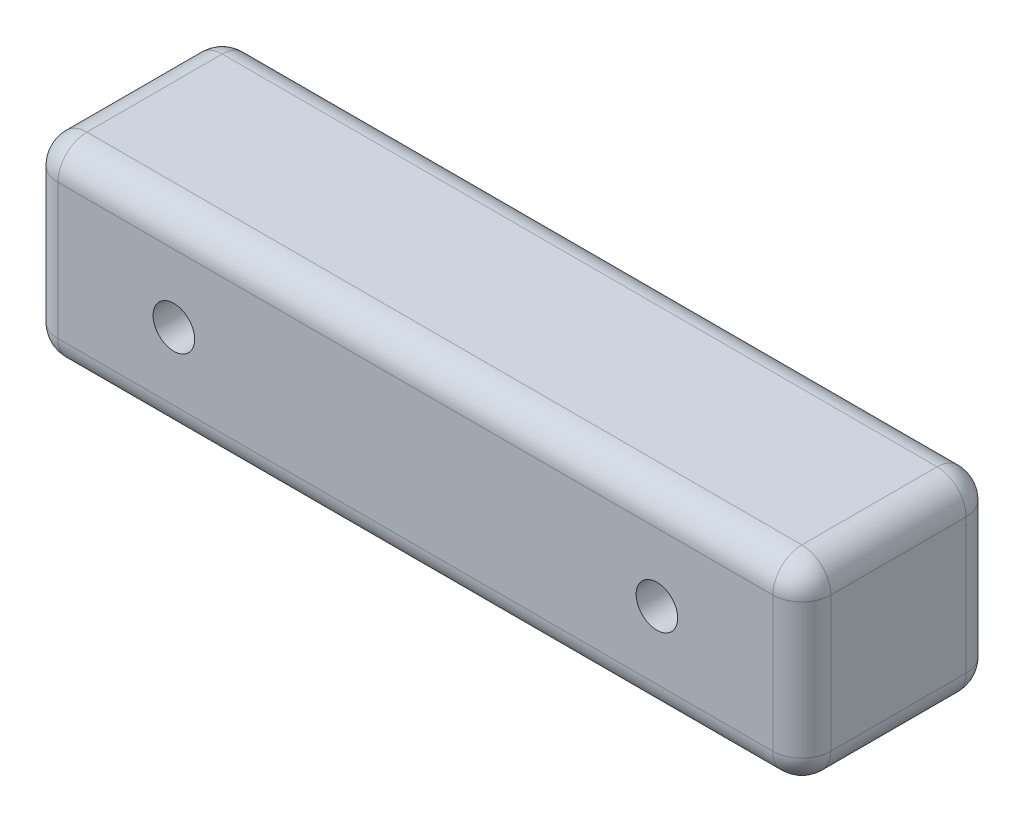
SolidWorks part; units mm, degrees
ref_plane "Alzado" through (0, 0, 0) normal (0, 0, 1) x (1, 0, 0)
ref_plane "Planta" through (0, 0, 0) normal (0, 1, 0) x (1, 0, 0)
ref_plane "Vista lateral" through (0, 0, 0) normal (1, 0, 0) x (0, 0, -1)
sketch "Croquis1" plane through (0, 0, 0) normal (0, 0, 1) x (1, 0, 0)
  line L0 (40, 0) -> (-40, 0) construction
  line L1 (-40, 10) -> (40, 10)
  line L2 (40, 10) -> (40, -10)
  line L3 (40, -10) -> (-40, -10)
  line L4 (-40, -10) -> (-40, 10)
  line L5 (0, 0) -> (0, -3.7626) construction
  circle A0 centre (25, 0) radius 2.15
  circle A1 centre (-25, 0) radius 2.15
  point P4 (0, 0)
  point P7 (-40, 0)
  dimension "D4" = 4.3
  dimension "D1" = 80
  dimension "D2" = 20
  dimension "D3" = 15
extrude "Saliente-Extruir1" add sketch "Croquis1" along normal blind 20
sketch "Croquis2" plane through (0, 0, 20) normal (0, 0, 1) x (1, 0, 0)
  line L0 (0, 0) -> (0, 5.7256) construction
  line L7 (20, -10) -> (40, -10)
  line L8 (20, 10) -> (20, -10)
  line L9 (40, 10) -> (20, 10)
  line L10 (40, -10) -> (40, 10)
  dimension "D1" = 20
extrude "Cortar-Extruir1" [suppressed] cut sketch "Croquis2" against normal blind 10
sketch "Croquis3" plane through (0, 0, 0) normal (0, 0, -1) x (-1, 0, 0)
  line L0 (40, 10) -> (20, 10)
  line L1 (-40, 10) -> (40, 10) construction
  line L2 (20, 10) -> (20, -10)
  line L3 (40, -10) -> (-40, -10) construction
  line L4 (20, -10) -> (40, -10)
  line L5 (40, -10) -> (40, 10)
  line L6 (-20, 10) -> (-20, -10)
  line L7 (-20, -10) -> (-40, -10)
  line L8 (-40, -10) -> (-40, 10)
  line L9 (-40, 10) -> (-20, 10)
  dimension "D1" = 20
  dimension "D2" = 20
extrude "Cortar-Extruir2" [suppressed] cut sketch "Croquis3" against normal blind 10
fillet "Redondeo1" radius 3 12 edges at (0, -10, 20) (-40, -10, 10) (-40, 0, 20) (0, 10, 20) (40, 0, 20) (40, -10, 10) (0, -10, 0) (-40, 0, 0) (-40, 10, 10) (40, 10, 10) (40, 0, 0) (0, 10, 0)
